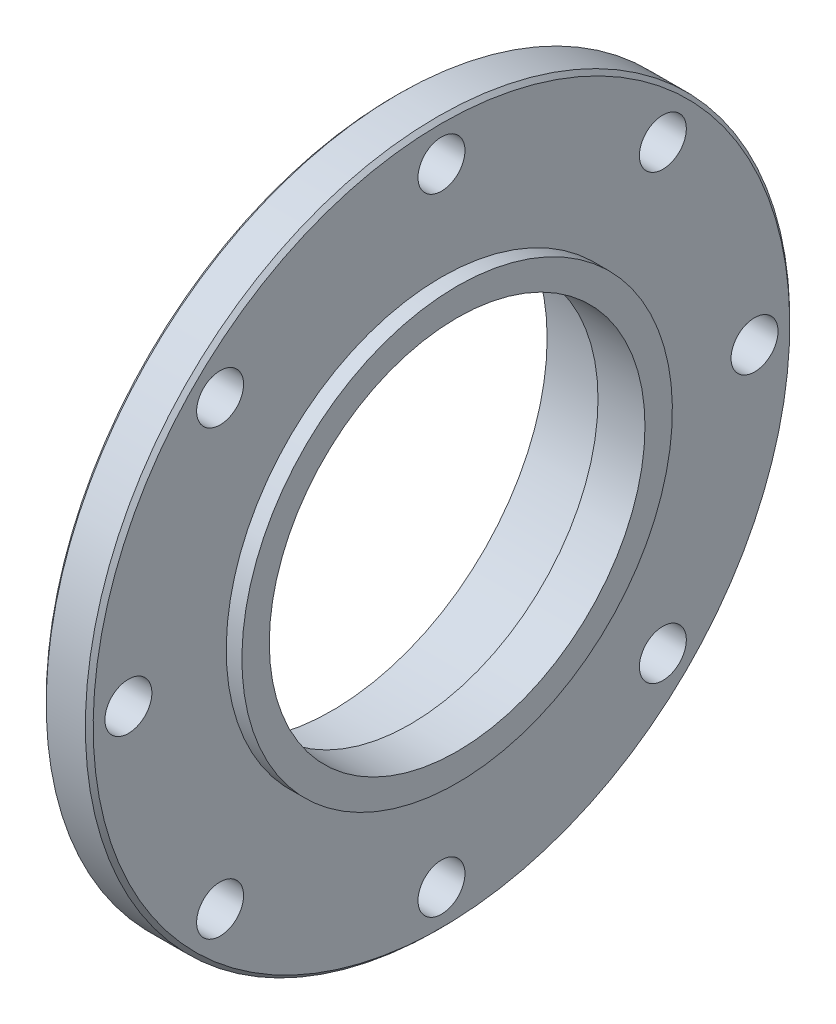
SolidWorks part; units mm, degrees
ref_plane "前视基准面" through (0, 0, 0) normal (0, 0, 1) x (1, 0, 0)
ref_plane "上视基准面" through (0, 0, 0) normal (0, 1, 0) x (1, 0, 0)
ref_plane "右视基准面" through (0, 0, 0) normal (1, 0, 0) x (0, 0, -1)
other "Configuration Table"
sketch "草图1" plane through (0, 0, 0) normal (0, 0, 1) x (1, 0, 0)
  line L0 (0, 0) -> (0, 30)
  line L1 (0, 30) -> (8, 30)
  line L2 (8, 30) -> (8, 45)
  line L3 (8, 45) -> (14, 45)
  line L4 (14, 45) -> (14, 27.5)
  line L5 (14, 27.5) -> (16, 27.5)
  line L6 (16, 27.5) -> (16, 0)
  line L7 (16, 0) -> (0, 0)
  dimension "D1" = 30
  dimension "D2" = 45
  dimension "D3" = 27.5
  dimension "D4" = 2
  dimension "D5" = 6
  dimension "D6" = 16
revolve "旋转1" add sketch "草图1" angle 360 about L7
sketch "草图2" plane through (0, 0, 0) normal (0, 0, 1) x (1, 0, 0)
  line L0 (0, 0) -> (0, 27.5)
  line L1 (0, 30) -> (0, -30) construction
  line L2 (0, 27.5) -> (10, 27.5)
  line L3 (10, 27.5) -> (10, 24)
  line L4 (10, 24) -> (16, 24)
  line L5 (16, -27.5) -> (16, 27.5) construction
  line L6 (16, 24) -> (16, 0)
  line L7 (16, 0) -> (0, 0)
  dimension "D1" = 27.5
  dimension "D2" = 24
  dimension "D3" = 10
revolve "切除-旋转1" cut sketch "草图2" angle 360 about L7
sketch "草图3" plane through (8, 0, 0) normal (-1, 0, 0) x (0, 0, 1)
  circle A0 centre (0, 0) radius 40 construction
  circle A1 centre (0, 40) radius 3
  circle A2 centre (28.2843, 28.2843) radius 3
  circle A3 centre (40, 0) radius 3
  circle A4 centre (28.2843, -28.2843) radius 3
  circle A5 centre (0, -40) radius 3
  circle A6 centre (-28.2843, -28.2843) radius 3
  circle A7 centre (-40, 0) radius 3
  circle A8 centre (-28.2843, 28.2843) radius 3
  point P22 (0, 0)
  dimension "D1" = 80
  dimension "D2" = 6
  dimension "D3" = 8
extrude "切除-拉伸1" cut sketch "草图3" against normal blind 10
chamfer "倒角1" distance 0.5 angle 45 3 edges at (0, 30, 0) (8, 45, 0) (14, 45, 0)
fillet "圆角1" radius 5 1 edges at (8, 30, 0)
